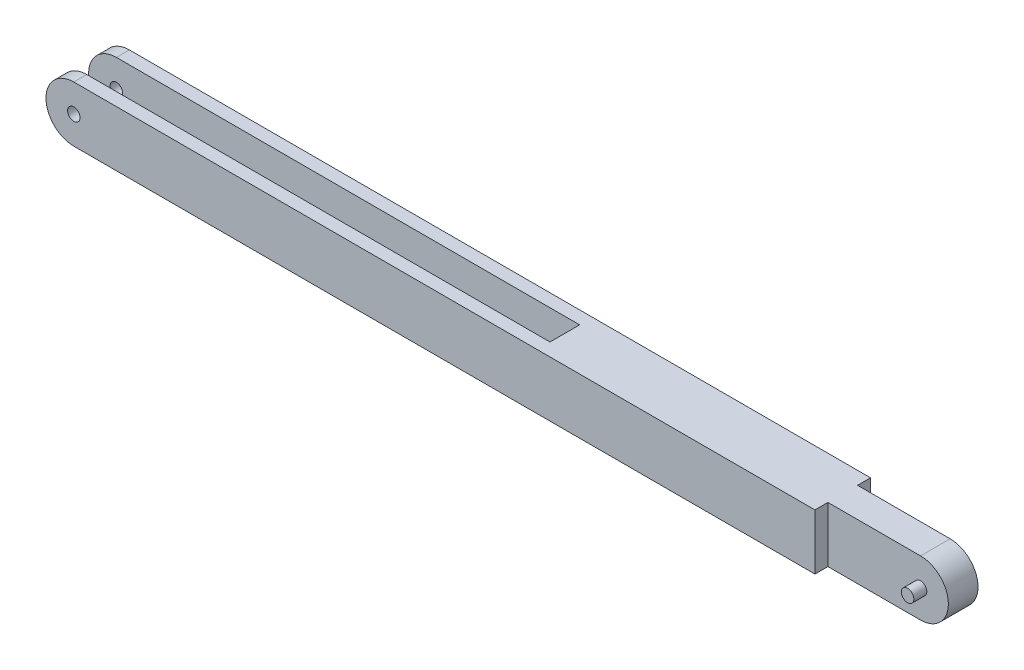
SolidWorks part; units mm, degrees
material "1060 Alloy"
ref_plane "Front Plane" through (0, 0, 0) normal (0, 0, 1) x (1, 0, 0)
ref_plane "Top Plane" through (0, 0, 0) normal (0, 1, 0) x (1, 0, 0)
ref_plane "Right Plane" through (0, 0, 0) normal (1, 0, 0) x (0, 0, -1)
sketch "Sketch1" plane through (0, 0, 0) normal (0, 0, 1) x (1, 0, 0)
  line L0 (-225, 0) -> (225, 0) construction
  line L1 (-225, 15) -> (225, 15)
  line L2 (-225, -15) -> (225, -15)
  arc A0 (-225, 15) -> (-225, -15) centre (-225, 0) ccw
  arc A1 (225, -15) -> (225, 15) centre (225, 0) ccw
  point P2 (0, 0)
  dimension "D1" = 450
  dimension "D2" = 30
extrude "Boss-Extrude1" add sketch "Sketch1" along normal mid plane 30
hole_wizard "H (0.266) Diameter Hole1" positions "Sketch2" profile "Sketch4" hole size "H" standard "ANSI Inch" end condition through all
sketch "Sketch2" plane through (0, 0, 15) normal (0, 0, 1) x (1, 0, 0)
  point P0 (-225, 0)
  point P3 (225, 0)
sketch "Sketch4" plane through (-225, 0, 15) normal (1, 0, 0) x (0, -1, 0)
  line L0 (0, 0) -> (0, 30)
  line L1 (0, 30) -> (3.3782, 30)
  line L2 (3.3782, 30) -> (3.3782, 0)
  line L5 (3.3782, 0) -> (0, 0)
  line L11 (0, -6.35) -> (0, 107.95) construction
  dimension "Thru Hole Dia." = 6.7564
  dimension "Thru Hole Depth" = 30
sketch "Sketch5" plane through (0, 15, 0) normal (0, 1, 0) x (1, 0, 0)
  line L0 (225, -15) -> (225, 15) construction
  line L1 (-975, 8) -> (25, 8)
  line L2 (-975, 8) -> (-975, -8)
  line L3 (-975, -8) -> (25, -8)
  line L4 (25, 8) -> (25, -8)
  line L5 (25, 0) -> (0, 0) construction
  line L6 (-225, -15) -> (-225, 15) construction
  line L8 (175, 28.9161) -> (245, 28.9161)
  line L9 (175, 28.9161) -> (175, 8)
  line L10 (175, 8) -> (245, 8)
  line L11 (245, 28.9161) -> (245, 8)
  line L12 (175, -28.9161) -> (245, -28.9161)
  line L13 (175, -28.9161) -> (175, -8)
  line L14 (175, -8) -> (245, -8)
  line L15 (245, -28.9161) -> (245, -8)
  dimension "D1" = 16
  dimension "D2" = 250
  dimension "D3" = 1000
  dimension "D4" = 20
  dimension "D5" = 70
extrude "Cut-Extrude1" cut sketch "Sketch5" against normal through all
sketch "Sketch6" plane through (0, 0, 0) normal (0, 0, 1) x (1, 0, 0)
  circle A0 centre (225, 0) radius 3.3782
extrude "Boss-Extrude4" add sketch "Sketch6" along normal up to surface and the other way up to surface up to face at (-28.75, 0, 15) other way up to face at (-221.6218, 0, -15)
